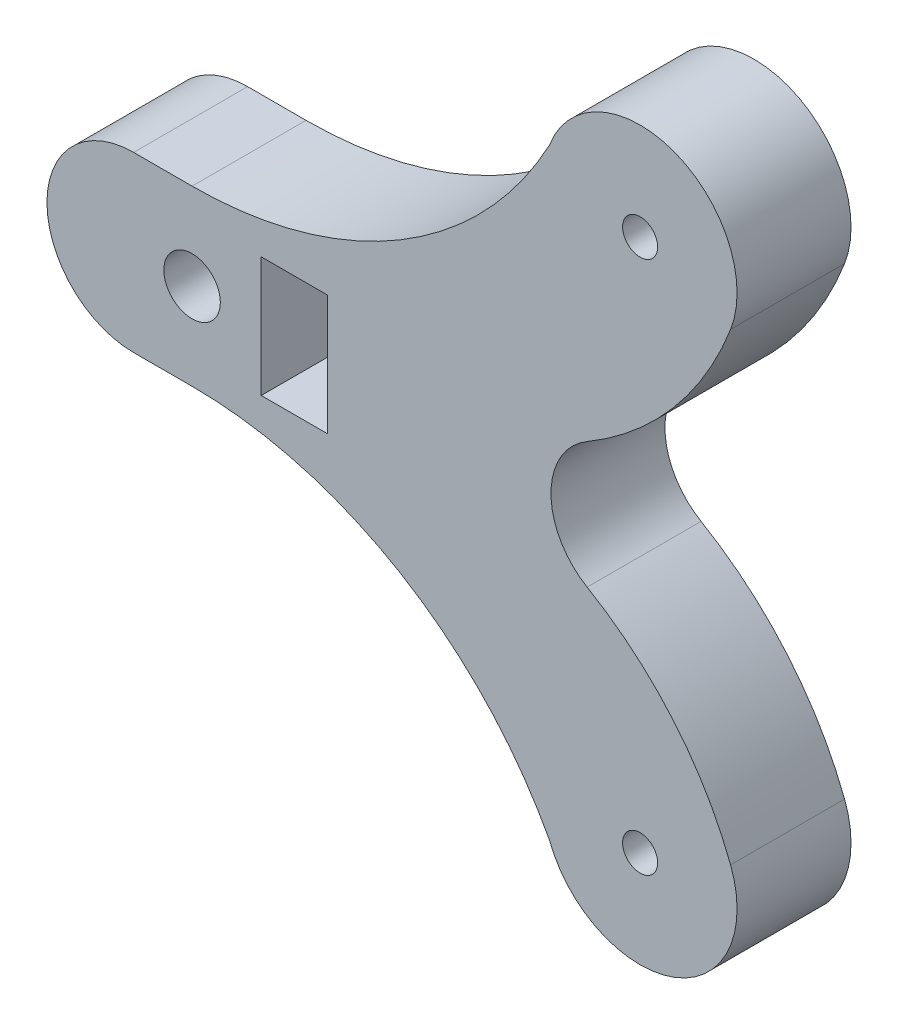
SolidWorks part; units mm, degrees
ref_plane "Front Plane" through (0, 0, 0) normal (0, 0, 1) x (1, 0, 0)
ref_plane "Top Plane" through (0, 0, 0) normal (0, 1, 0) x (1, 0, 0)
ref_plane "Right Plane" through (0, 0, 0) normal (1, 0, 0) x (0, 0, -1)
sketch "Sketch1" plane through (0, 0, 0) normal (0, 0, 1) x (1, 0, 0)
  line L0 (587.4699, 435.3658) -> (584.4699, 435.3658) construction
  line L1 (594.1695, 438.4484) -> (594.1695, 432.2832) construction
  line L2 (592.4695, 438.4484) -> (595.8695, 438.4484)
  line L3 (595.8695, 438.4484) -> (595.8695, 432.2832)
  line L4 (595.8695, 432.2832) -> (592.4695, 432.2832)
  line L5 (592.4695, 432.2832) -> (592.4695, 438.4484)
  line L6 (588.9197, 433.916) -> (588.9197, 430.916) construction
  line L7 (588.9197, 436.8156) -> (588.9197, 439.8156) construction
  line L8 (592.4695, 435.3658) -> (595.8695, 435.3658) construction
  line L9 (588.9197, 439.8156) -> (585.9197, 439.8156)
  line L10 (611.9197, 449.0571) -> (611.9197, 421.6746) construction
  line L11 (611.9197, 421.6746) -> (611.9197, 424.6498) construction
  line L13 (611.9197, 421.6746) -> (611.9197, 418.6993) construction
  line L14 (588.9197, 430.916) -> (585.9197, 430.916)
  line L16 (611.9197, 449.0571) -> (611.9197, 452.0323) construction
  line L17 (611.9197, 449.0571) -> (611.9197, 446.0819) construction
  line L20 (607.1695, 435.4045) -> (50607.1695, 435.4045) construction
  circle A0 centre (611.9197, 449.0571) radius 0.9
  circle A1 centre (611.9197, 421.6746) radius 0.9
  circle A2 centre (588.9197, 435.3658) radius 1.4498
  arc A3 (585.9197, 439.8156) -> (585.9197, 430.916) centre (585.9197, 435.3658) ccw
  arc A4 (607.2581, 450.8017) -> (616.5644, 447.2679) centre (611.9197, 449.0571) cw
  arc A5 (588.9197, 439.8156) -> (607.2581, 450.8017) centre (588.9197, 460.6142) ccw
  arc A6 (609.1999, 438.6032) -> (609.1999, 432.1285) centre (611.0947, 435.3658) ccw
  arc A7 (609.1999, 438.6032) -> (616.5644, 447.2679) centre (600.5082, 453.4528) ccw
  arc A8 (609.1999, 432.1285) -> (616.5644, 423.4637) centre (600.5082, 417.2789) cw
  arc A9 (607.2581, 419.9299) -> (616.5644, 423.4637) centre (611.9197, 421.6746) ccw
  arc A10 (588.9197, 430.916) -> (607.2581, 419.9299) centre (588.9197, 410.1175) cw
  point P35 (590.3695, 435.3658)
  dimension "D1" = 2.1
  dimension "D2" = 23
extrude "Boss-Extrude1" add sketch "Sketch1" along normal blind 5.85
